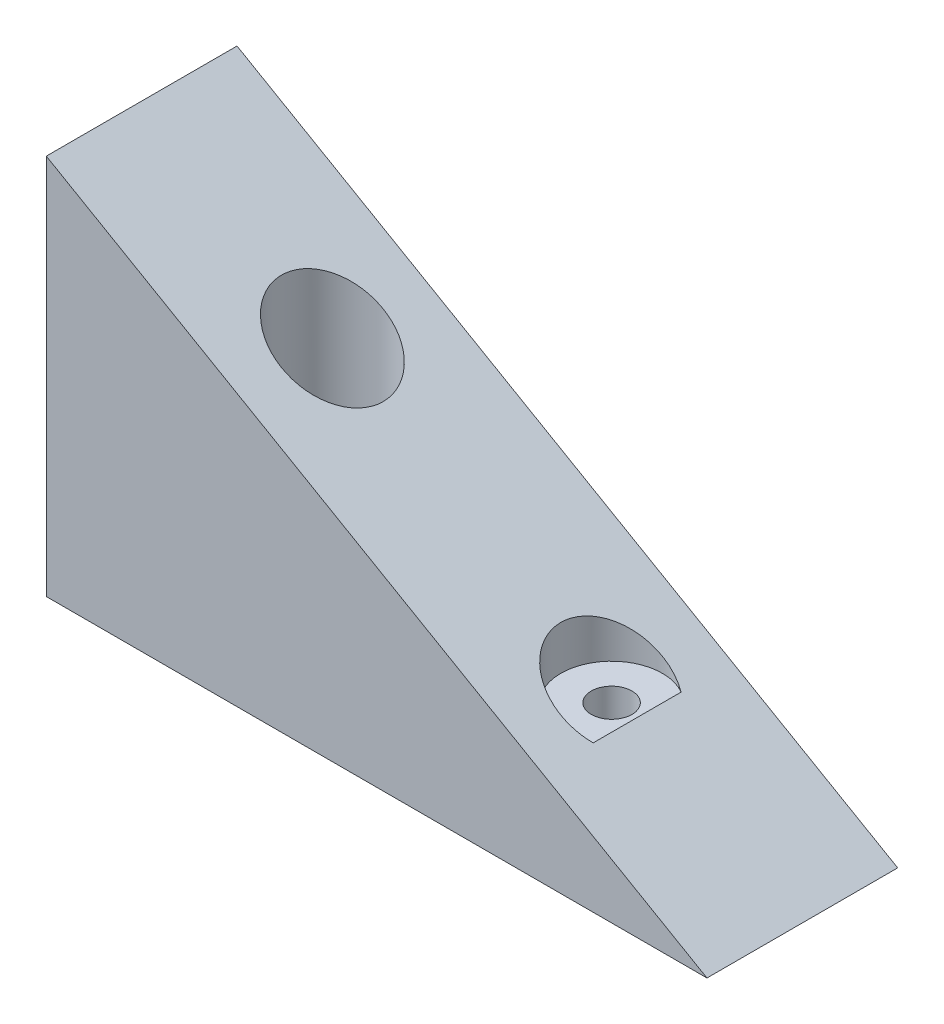
SolidWorks part; units mm, degrees
ref_plane "Front" through (0, 0, 0) normal (0, 0, 1) x (1, 0, 0)
ref_plane "Top" through (0, 0, 0) normal (0, 1, 0) x (1, 0, 0)
ref_plane "Right" through (0, 0, 0) normal (1, 0, 0) x (0, 0, -1)
sketch "ｽｹｯﾁ1" plane through (0, 0, 0) normal (0, 0, 1) x (1, 0, 0)
  line L0 (-25.9808, 15) -> (25.9808, -15)
  line L1 (-25.9808, 15) -> (25.9808, 15)
  line L2 (-25.9808, 15) -> (-25.9808, -15)
  line L3 (-25.9808, -15) -> (25.9808, -15)
  line L4 (25.9808, 15) -> (25.9808, -15)
  line L5 (0, -15) -> (0, 15) construction
  line L6 (-25.9808, 0) -> (25.9808, 0) construction
  point P0 (0, 0)
  point P6 (0, 0)
  dimension "D1" = 60
  dimension "D2" = 30
extrude "ﾎﾞｽ - 押し出し1" add sketch "ｽｹｯﾁ1" along normal blind 15 contours L2 L3 L0
sketch "ｽｹｯﾁ2" plane through (0, -15, 0) normal (0, -1, 0) x (1, 0, 0)
  line L0 (-25.9808, 0) -> (25.9808, 0) construction
  line L1 (25.9808, 15) -> (25.9808, 0) construction
  line L2 (-25.9808, 15) -> (-25.9808, 0) construction
  circle A0 centre (-10.9808, 7.5) radius 1.6
  circle A1 centre (10.9808, 7.5) radius 1.6
  dimension "D1" = 7.5
  dimension "D2" = 7.5
  dimension "D3" = 15
  dimension "D4" = 15
  dimension "D5" = 3.2
  dimension "D6" = 3.2
  dimension "D7" = 21.9615
extrude "ｶｯﾄ - 押し出し1" cut sketch "ｽｹｯﾁ2" against normal through all
sketch "ｽｹｯﾁ3" plane through (0, 0, 0) normal (0, 1, 0) x (1, 0, 0)
  circle A0 centre (10.9808, -7.5) radius 1.6 construction
  circle A1 centre (-10.9808, -7.5) radius 1.6 construction
  circle A2 centre (10.9808, -7.5) radius 1.6
  circle A3 centre (-10.9808, -7.5) radius 1.6
  circle A4 centre (-10.9808, -7.5) radius 4
  circle A5 centre (10.9808, -7.5) radius 4
  dimension "D1" = 8
  dimension "D2" = 8
extrude "ｶｯﾄ - 押し出し2" cut sketch "ｽｹｯﾁ3" against normal blind 7.5 and the other way through all
